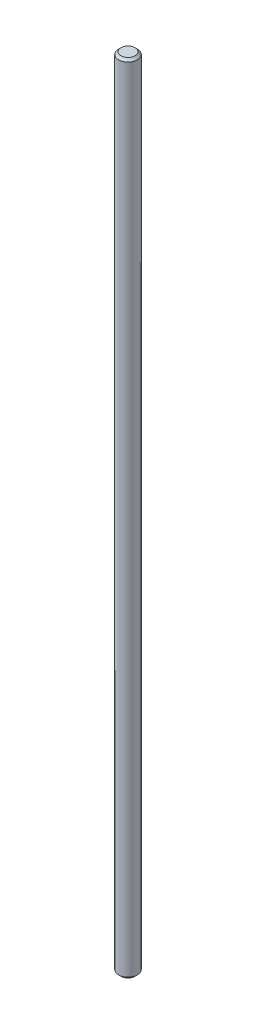
SolidWorks part; units mm, degrees
ref_plane "Front Plane" through (0, 0, 0) normal (0, 0, 1) x (1, 0, 0)
ref_plane "Top Plane" through (0, 0, 0) normal (0, 1, 0) x (1, 0, 0)
ref_plane "Right Plane" through (0, 0, 0) normal (1, 0, 0) x (0, 0, -1)
ref_plane "Plane1" through (0, 340, 0) normal (0, 1, 0) x (1, 0, 0)
sketch "Sketch1" plane through (0, 340, 0) normal (0, 1, 0) x (1, 0, 0)
  circle A0 centre (0, 0) radius 4
extrude "Boss-Extrude1" add sketch "Sketch1" against normal blind 340
chamfer "Chamfer1" distance 1 angle 45 2 edges at (0, 0, -4) (0, 340, -4)
